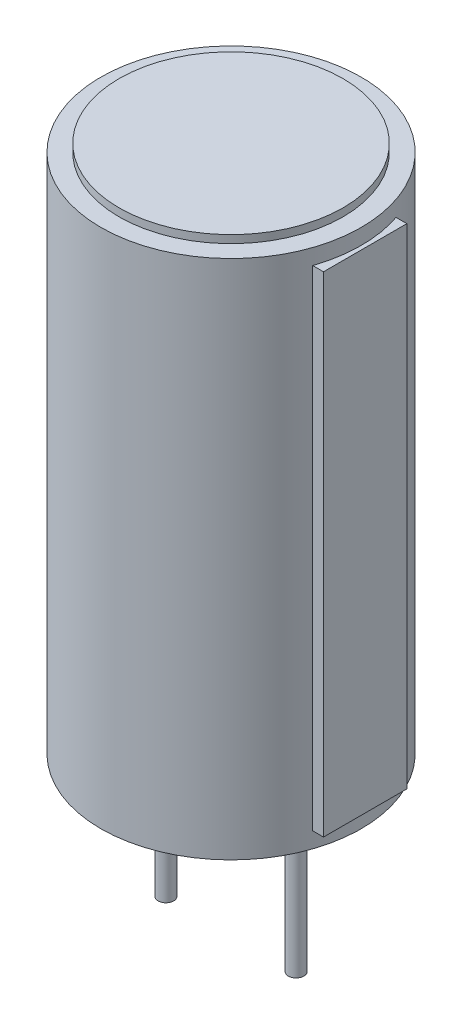
SolidWorks part; units mm, degrees
ref_plane "Front Plane" through (0, 0, 0) normal (0, 0, 1) x (1, 0, 0)
ref_plane "Top Plane" through (0, 0, 0) normal (0, 1, 0) x (1, 0, 0)
ref_plane "Right Plane" through (0, 0, 0) normal (1, 0, 0) x (0, 0, -1)
sketch "SK Can" plane through (0, 0, 0) normal (0, 1, 0) x (1, 0, 0)
  circle A0 centre (0, 0) radius 5
extrude "Can" add sketch "SK Can" along normal blind 20 separate body
sketch "SK Top disc" plane through (0, 0, 0) normal (0, 1, 0) x (1, 0, 0)
  circle A0 centre (0, 0) radius 4.3
extrude "Top disc" add sketch "SK Top disc" along normal blind 0.3 from offset 20 separate body
sketch "SK Minus stripe" plane through (0, 0, 0) normal (0, 1, 0) x (1, 0, 0)
  line L1 (4.6, 1.6) -> (5.15, 1.6)
  line L2 (4.6, 1.6) -> (4.6, -1.6)
  line L3 (4.6, -1.6) -> (5.15, -1.6)
  line L4 (5.15, 1.6) -> (5.15, -1.6)
extrude "Minus stripe" add sketch "SK Minus stripe" along normal blind 18.8 from offset 0.6 separate body
sketch "SK Leads" plane through (0, 0, 0) normal (0, 1, 0) x (1, 0, 0)
  circle A0 centre (-2.5, 0) radius 0.3
  circle A1 centre (2.5, 0) radius 0.3
extrude "Leads" add sketch "SK Leads" along normal blind 6 from offset 6 separate body
